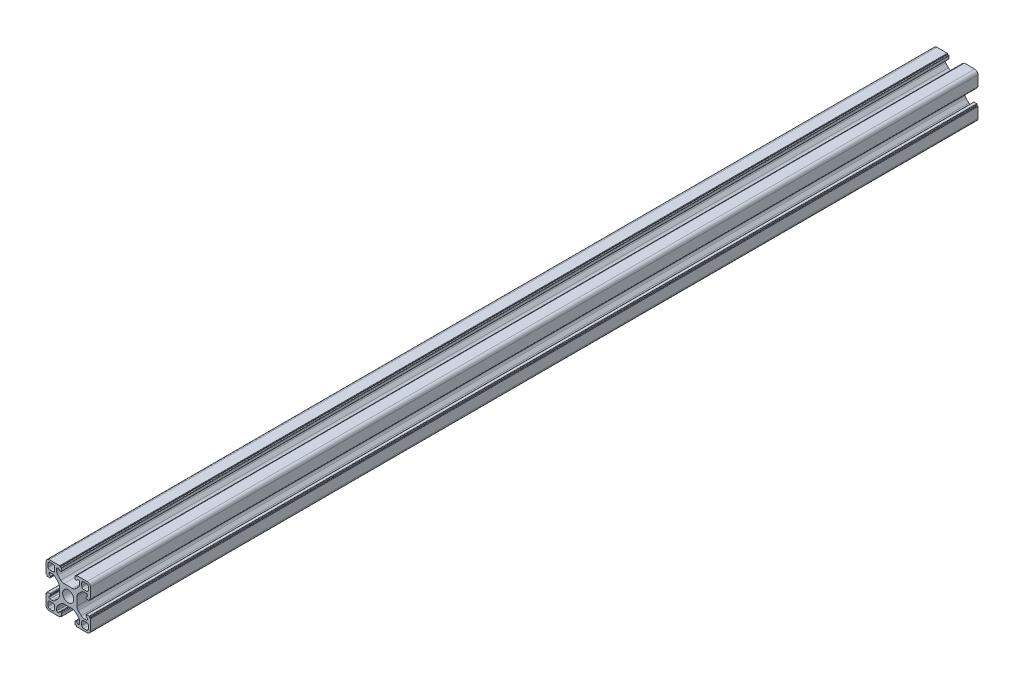
SolidWorks part; units mm, degrees
material "1060 Сплав"
ref_plane "Спереди" through (0, 0, 0) normal (0, 0, 1) x (1, 0, 0)
ref_plane "Сверху" through (0, 0, 0) normal (0, 1, 0) x (1, 0, 0)
ref_plane "Справа" through (0, 0, 0) normal (1, 0, 0) x (0, 0, -1)
sketch "Эскиз1" plane through (0, 0, 0) normal (0, 0, 1) x (1, 0, 0)
  line L0 (-22.0052, 70.3096) -> (-25.0052, 67.3096) construction
  line L1 (-31.1052, 65.2096) -> (-29.2064, 65.2096)
  line L2 (-31.1052, 61.2096) -> (-21.1052, 71.2096) construction
  line L3 (-23.5052, 68.8096) -> (-25.0052, 70.3096) construction
  line L4 (-27.7922, 65.7954) -> (-26.4909, 67.0967)
  line L5 (-24.2052, 67.3096) -> (-22.8052, 67.3096)
  line L6 (-25.0052, 68.1096) -> (-25.0052, 69.5096)
  line L7 (-22.8052, 70.3096) -> (-24.2052, 70.3096)
  line L8 (-25.9052, 69.4096) -> (-25.9052, 68.5109)
  line L9 (-27.3419, 69.2829) -> (-26.8616, 69.7632)
  line L10 (-27.9052, 70.7587) -> (-27.4052, 70.7587)
  line L11 (-27.5187, 69.2096) -> (-27.8052, 69.2096)
  line L12 (-26.508, 69.9096) -> (-26.4052, 69.9096)
  line L13 (-27.4052, 71.0596) -> (-27.4052, 70.7587)
  line L14 (-28.0552, 70.6087) -> (-28.0552, 69.4596)
  line L15 (-22.6052, 71.2096) -> (-27.2552, 71.2096)
  line L16 (-22.0052, 69.5096) -> (-22.0052, 68.1096)
  line L17 (-21.1052, 69.7096) -> (-21.1052, 65.0596)
  line L18 (-21.7061, 64.2596) -> (-22.8552, 64.2596)
  line L19 (-21.2552, 64.9096) -> (-21.5561, 64.9096)
  line L20 (-22.4052, 65.8068) -> (-22.4052, 65.9096)
  line L21 (-23.1052, 64.7961) -> (-23.1052, 64.5096)
  line L22 (-21.5561, 64.4096) -> (-21.5561, 64.9096)
  line L23 (-23.0319, 64.9729) -> (-22.5516, 65.4532)
  line L24 (-22.9052, 66.4096) -> (-23.8039, 66.4096)
  line L25 (-26.5194, 64.5226) -> (-25.2181, 65.8239)
  line L26 (-27.1052, 61.2096) -> (-27.1052, 63.1084)
  line L27 (-27.1052, 61.2096) -> (-27.1052, 59.3109)
  line L28 (-26.5194, 57.8967) -> (-25.2181, 56.5954)
  line L29 (-25.0052, 54.3096) -> (-25.0052, 52.9096)
  line L30 (-24.2052, 55.1096) -> (-22.8052, 55.1096)
  line L31 (-22.0052, 52.9096) -> (-22.0052, 54.3096)
  line L32 (-22.9052, 56.0096) -> (-23.8039, 56.0096)
  line L33 (-23.0319, 57.4464) -> (-22.5516, 56.9661)
  line L34 (-21.5561, 58.0096) -> (-21.5561, 57.5096)
  line L35 (-23.1052, 57.6232) -> (-23.1052, 57.9096)
  line L36 (-22.4052, 56.6125) -> (-22.4052, 56.5096)
  line L37 (-21.2552, 57.5096) -> (-21.5561, 57.5096)
  line L38 (-21.7061, 58.1596) -> (-22.8552, 58.1596)
  line L39 (-21.1052, 52.7096) -> (-21.1052, 57.3596)
  line L40 (-22.8052, 52.1096) -> (-24.2052, 52.1096)
  line L41 (-22.6052, 51.2096) -> (-27.2552, 51.2096)
  line L42 (-28.0552, 51.8106) -> (-28.0552, 52.9596)
  line L43 (-27.4052, 51.3596) -> (-27.4052, 51.6606)
  line L44 (-26.508, 52.5096) -> (-26.4052, 52.5096)
  line L45 (-27.5187, 53.2096) -> (-27.8052, 53.2096)
  line L46 (-27.9052, 51.6606) -> (-27.4052, 51.6606)
  line L47 (-27.3419, 53.1364) -> (-26.8616, 52.6561)
  line L48 (-25.9052, 53.0096) -> (-25.9052, 53.9084)
  line L49 (-27.7922, 56.6239) -> (-26.4909, 55.3226)
  line L50 (-31.1052, 57.2096) -> (-29.2064, 57.2096)
  line L51 (-22.0052, 52.1096) -> (-25.0052, 55.1096) construction
  line L52 (-31.1052, 61.2096) -> (-21.1052, 51.2096) construction
  line L53 (-23.5052, 53.6096) -> (-22.0052, 55.1096) construction
  line L54 (-31.1052, 57.2096) -> (-33.0039, 57.2096)
  line L55 (-34.4181, 56.6239) -> (-35.7194, 55.3226)
  line L56 (-38.0052, 55.1096) -> (-39.4052, 55.1096)
  line L57 (-37.2052, 54.3096) -> (-37.2052, 52.9096)
  line L58 (-39.4052, 52.1096) -> (-38.0052, 52.1096)
  line L59 (-36.3052, 53.0096) -> (-36.3052, 53.9084)
  line L60 (-34.8684, 53.1364) -> (-35.3487, 52.6561)
  line L61 (-34.3052, 51.6606) -> (-34.8052, 51.6606)
  line L62 (-34.6916, 53.2096) -> (-34.4052, 53.2096)
  line L63 (-35.7023, 52.5096) -> (-35.8052, 52.5096)
  line L64 (-34.8052, 51.3596) -> (-34.8052, 51.6606)
  line L65 (-34.1552, 51.8106) -> (-34.1552, 52.9596)
  line L66 (-39.6052, 51.2096) -> (-34.9552, 51.2096)
  line L67 (-40.2052, 52.9096) -> (-40.2052, 54.3096)
  line L68 (-41.1052, 52.7096) -> (-41.1052, 57.3596)
  line L69 (-40.5042, 58.1596) -> (-39.3552, 58.1596)
  line L70 (-40.9552, 57.5096) -> (-40.6542, 57.5096)
  line L71 (-39.8052, 56.6125) -> (-39.8052, 56.5096)
  line L72 (-39.1052, 57.6232) -> (-39.1052, 57.9096)
  line L73 (-40.6542, 58.0096) -> (-40.6542, 57.5096)
  line L74 (-39.1784, 57.4464) -> (-39.6587, 56.9661)
  line L75 (-39.3052, 56.0096) -> (-38.4064, 56.0096)
  line L76 (-35.6909, 57.8967) -> (-36.9922, 56.5954)
  line L77 (-35.1052, 61.2096) -> (-35.1052, 59.3109)
  line L78 (-40.2052, 52.1096) -> (-37.2052, 55.1096) construction
  line L79 (-31.1052, 61.2096) -> (-41.1052, 51.2096) construction
  line L80 (-38.7052, 53.6096) -> (-37.2052, 52.1096) construction
  line L81 (-35.1052, 61.2096) -> (-35.1052, 63.1084)
  line L82 (-35.6909, 64.5226) -> (-36.9922, 65.8239)
  line L83 (-37.2052, 68.1096) -> (-37.2052, 69.5096)
  line L84 (-38.0052, 67.3096) -> (-39.4052, 67.3096)
  line L85 (-40.2052, 69.5096) -> (-40.2052, 68.1096)
  line L86 (-39.3052, 66.4096) -> (-38.4064, 66.4096)
  line L87 (-39.1784, 64.9729) -> (-39.6587, 65.4532)
  line L88 (-40.6542, 64.4096) -> (-40.6542, 64.9096)
  line L89 (-39.1052, 64.7961) -> (-39.1052, 64.5096)
  line L90 (-39.8052, 65.8068) -> (-39.8052, 65.9096)
  line L91 (-40.9552, 64.9096) -> (-40.6542, 64.9096)
  line L92 (-40.5042, 64.2596) -> (-39.3552, 64.2596)
  line L93 (-41.1052, 69.7096) -> (-41.1052, 65.0596)
  line L94 (-39.4052, 70.3096) -> (-38.0052, 70.3096)
  line L95 (-39.6052, 71.2096) -> (-34.9552, 71.2096)
  line L96 (-34.1552, 70.6087) -> (-34.1552, 69.4596)
  line L97 (-34.8052, 71.0596) -> (-34.8052, 70.7587)
  line L98 (-35.7023, 69.9096) -> (-35.8052, 69.9096)
  line L99 (-34.6916, 69.2096) -> (-34.4052, 69.2096)
  line L100 (-34.3052, 70.7587) -> (-34.8052, 70.7587)
  line L101 (-34.8684, 69.2829) -> (-35.3487, 69.7632)
  line L102 (-36.3052, 69.4096) -> (-36.3052, 68.5109)
  line L103 (-34.4181, 65.7954) -> (-35.7194, 67.0967)
  line L104 (-31.1052, 65.2096) -> (-33.0039, 65.2096)
  line L105 (-42.8692, 61.2096) -> (-19.6008, 61.2096) construction
  line L106 (-40.2052, 70.3096) -> (-37.2052, 67.3096) construction
  line L107 (-31.1052, 49.1232) -> (-31.1052, 71.9286) construction
  line L108 (-31.1052, 61.2096) -> (-41.1052, 71.2096) construction
  line L109 (-38.7052, 68.8096) -> (-40.2052, 67.3096) construction
  arc A0 (-22.0052, 69.5096) -> (-22.8052, 70.3096) centre (-22.8052, 69.5096) ccw
  arc A1 (-24.2052, 70.3096) -> (-25.0052, 69.5096) centre (-24.2052, 69.5096) ccw
  arc A2 (-24.2052, 67.3096) -> (-25.0052, 68.1096) centre (-24.2052, 68.1096) cw
  arc A3 (-22.6052, 71.2096) -> (-21.1052, 69.7096) centre (-22.6052, 69.7096) cw
  arc A4 (-27.9052, 70.7587) -> (-28.0552, 70.6087) centre (-27.9052, 70.6087) ccw
  arc A5 (-27.2552, 71.2096) -> (-27.4052, 71.0596) centre (-27.2552, 71.0596) ccw
  arc A6 (-27.5187, 69.2096) -> (-27.3419, 69.2829) centre (-27.5187, 69.4596) ccw
  arc A7 (-27.8052, 69.2096) -> (-28.0552, 69.4596) centre (-27.8052, 69.4596) cw
  arc A8 (-26.8616, 69.7632) -> (-26.508, 69.9096) centre (-26.508, 69.4096) cw
  arc A9 (-26.4052, 69.9096) -> (-25.9052, 69.4096) centre (-26.4052, 69.4096) cw
  arc A10 (-28.6052, 61.2096) -> (-31.1052, 63.7096) centre (-31.1052, 61.2096) ccw
  arc A11 (-29.2064, 65.2096) -> (-27.7922, 65.7954) centre (-29.2064, 67.2096) ccw
  arc A12 (-25.9052, 68.5109) -> (-26.4909, 67.0967) centre (-27.9052, 68.5109) cw
  arc A13 (-22.0052, 68.1096) -> (-22.8052, 67.3096) centre (-22.8052, 68.1096) cw
  arc A14 (-22.4052, 65.9096) -> (-22.9052, 66.4096) centre (-22.9052, 65.9096) ccw
  arc A15 (-22.5516, 65.4532) -> (-22.4052, 65.8068) centre (-22.9052, 65.8068) ccw
  arc A16 (-23.1052, 64.5096) -> (-22.8552, 64.2596) centre (-22.8552, 64.5096) ccw
  arc A17 (-23.1052, 64.7961) -> (-23.0319, 64.9729) centre (-22.8552, 64.7961) cw
  arc A18 (-21.1052, 65.0596) -> (-21.2552, 64.9096) centre (-21.2552, 65.0596) cw
  arc A19 (-21.5561, 64.4096) -> (-21.7061, 64.2596) centre (-21.7061, 64.4096) cw
  arc A20 (-23.8039, 66.4096) -> (-25.2181, 65.8239) centre (-23.8039, 64.4096) ccw
  arc A21 (-27.1052, 63.1084) -> (-26.5194, 64.5226) centre (-25.1052, 63.1084) cw
  arc A22 (-22.8052, 52.1096) -> (-22.0052, 52.9096) centre (-22.8052, 52.9096) ccw
  arc A23 (-22.0052, 54.3096) -> (-22.8052, 55.1096) centre (-22.8052, 54.3096) ccw
  arc A24 (-25.0052, 54.3096) -> (-24.2052, 55.1096) centre (-24.2052, 54.3096) cw
  arc A25 (-21.1052, 52.7096) -> (-22.6052, 51.2096) centre (-22.6052, 52.7096) cw
  arc A26 (-21.5561, 58.0096) -> (-21.7061, 58.1596) centre (-21.7061, 58.0096) ccw
  arc A27 (-21.1052, 57.3596) -> (-21.2552, 57.5096) centre (-21.2552, 57.3596) ccw
  arc A28 (-23.1052, 57.6232) -> (-23.0319, 57.4464) centre (-22.8552, 57.6232) ccw
  arc A29 (-23.1052, 57.9096) -> (-22.8552, 58.1596) centre (-22.8552, 57.9096) cw
  arc A30 (-22.5516, 56.9661) -> (-22.4052, 56.6125) centre (-22.9052, 56.6125) cw
  arc A31 (-22.4052, 56.5096) -> (-22.9052, 56.0096) centre (-22.9052, 56.5096) cw
  arc A32 (-31.1052, 58.7096) -> (-28.6052, 61.2096) centre (-31.1052, 61.2096) ccw
  arc A33 (-27.1052, 59.3109) -> (-26.5194, 57.8967) centre (-25.1052, 59.3109) ccw
  arc A34 (-23.8039, 56.0096) -> (-25.2181, 56.5954) centre (-23.8039, 58.0096) cw
  arc A35 (-24.2052, 52.1096) -> (-25.0052, 52.9096) centre (-24.2052, 52.9096) cw
  arc A36 (-26.4052, 52.5096) -> (-25.9052, 53.0096) centre (-26.4052, 53.0096) ccw
  arc A37 (-26.8616, 52.6561) -> (-26.508, 52.5096) centre (-26.508, 53.0096) ccw
  arc A38 (-27.8052, 53.2096) -> (-28.0552, 52.9596) centre (-27.8052, 52.9596) ccw
  arc A39 (-27.5187, 53.2096) -> (-27.3419, 53.1364) centre (-27.5187, 52.9596) cw
  arc A40 (-27.2552, 51.2096) -> (-27.4052, 51.3596) centre (-27.2552, 51.3596) cw
  arc A41 (-27.9052, 51.6606) -> (-28.0552, 51.8106) centre (-27.9052, 51.8106) cw
  arc A42 (-25.9052, 53.9084) -> (-26.4909, 55.3226) centre (-27.9052, 53.9084) ccw
  arc A43 (-29.2064, 57.2096) -> (-27.7922, 56.6239) centre (-29.2064, 55.2096) cw
  arc A44 (-40.2052, 52.9096) -> (-39.4052, 52.1096) centre (-39.4052, 52.9096) ccw
  arc A45 (-38.0052, 52.1096) -> (-37.2052, 52.9096) centre (-38.0052, 52.9096) ccw
  arc A46 (-38.0052, 55.1096) -> (-37.2052, 54.3096) centre (-38.0052, 54.3096) cw
  arc A47 (-39.6052, 51.2096) -> (-41.1052, 52.7096) centre (-39.6052, 52.7096) cw
  arc A48 (-34.3052, 51.6606) -> (-34.1552, 51.8106) centre (-34.3052, 51.8106) ccw
  arc A49 (-34.9552, 51.2096) -> (-34.8052, 51.3596) centre (-34.9552, 51.3596) ccw
  arc A50 (-34.6916, 53.2096) -> (-34.8684, 53.1364) centre (-34.6916, 52.9596) ccw
  arc A51 (-34.4052, 53.2096) -> (-34.1552, 52.9596) centre (-34.4052, 52.9596) cw
  arc A52 (-35.3487, 52.6561) -> (-35.7023, 52.5096) centre (-35.7023, 53.0096) cw
  arc A53 (-35.8052, 52.5096) -> (-36.3052, 53.0096) centre (-35.8052, 53.0096) cw
  arc A54 (-33.6052, 61.2096) -> (-31.1052, 58.7096) centre (-31.1052, 61.2096) ccw
  arc A55 (-33.0039, 57.2096) -> (-34.4181, 56.6239) centre (-33.0039, 55.2096) ccw
  arc A56 (-36.3052, 53.9084) -> (-35.7194, 55.3226) centre (-34.3052, 53.9084) cw
  arc A57 (-40.2052, 54.3096) -> (-39.4052, 55.1096) centre (-39.4052, 54.3096) cw
  arc A58 (-39.8052, 56.5096) -> (-39.3052, 56.0096) centre (-39.3052, 56.5096) ccw
  arc A59 (-39.6587, 56.9661) -> (-39.8052, 56.6125) centre (-39.3052, 56.6125) ccw
  arc A60 (-39.1052, 57.9096) -> (-39.3552, 58.1596) centre (-39.3552, 57.9096) ccw
  arc A61 (-39.1052, 57.6232) -> (-39.1784, 57.4464) centre (-39.3552, 57.6232) cw
  arc A62 (-41.1052, 57.3596) -> (-40.9552, 57.5096) centre (-40.9552, 57.3596) cw
  arc A63 (-40.6542, 58.0096) -> (-40.5042, 58.1596) centre (-40.5042, 58.0096) cw
  arc A64 (-38.4064, 56.0096) -> (-36.9922, 56.5954) centre (-38.4064, 58.0096) ccw
  arc A65 (-35.1052, 59.3109) -> (-35.6909, 57.8967) centre (-37.1052, 59.3109) cw
  arc A66 (-39.4052, 70.3096) -> (-40.2052, 69.5096) centre (-39.4052, 69.5096) ccw
  arc A67 (-40.2052, 68.1096) -> (-39.4052, 67.3096) centre (-39.4052, 68.1096) ccw
  arc A68 (-37.2052, 68.1096) -> (-38.0052, 67.3096) centre (-38.0052, 68.1096) cw
  arc A69 (-41.1052, 69.7096) -> (-39.6052, 71.2096) centre (-39.6052, 69.7096) cw
  arc A70 (-40.6542, 64.4096) -> (-40.5042, 64.2596) centre (-40.5042, 64.4096) ccw
  arc A71 (-41.1052, 65.0596) -> (-40.9552, 64.9096) centre (-40.9552, 65.0596) ccw
  arc A72 (-39.1052, 64.7961) -> (-39.1784, 64.9729) centre (-39.3552, 64.7961) ccw
  arc A73 (-39.1052, 64.5096) -> (-39.3552, 64.2596) centre (-39.3552, 64.5096) cw
  arc A74 (-39.6587, 65.4532) -> (-39.8052, 65.8068) centre (-39.3052, 65.8068) cw
  arc A75 (-39.8052, 65.9096) -> (-39.3052, 66.4096) centre (-39.3052, 65.9096) cw
  arc A76 (-31.1052, 63.7096) -> (-33.6052, 61.2096) centre (-31.1052, 61.2096) ccw
  arc A77 (-35.1052, 63.1084) -> (-35.6909, 64.5226) centre (-37.1052, 63.1084) ccw
  arc A78 (-38.4064, 66.4096) -> (-36.9922, 65.8239) centre (-38.4064, 64.4096) cw
  arc A79 (-38.0052, 70.3096) -> (-37.2052, 69.5096) centre (-38.0052, 69.5096) cw
  arc A80 (-35.8052, 69.9096) -> (-36.3052, 69.4096) centre (-35.8052, 69.4096) ccw
  arc A81 (-35.3487, 69.7632) -> (-35.7023, 69.9096) centre (-35.7023, 69.4096) ccw
  arc A82 (-34.4052, 69.2096) -> (-34.1552, 69.4596) centre (-34.4052, 69.4596) ccw
  arc A83 (-34.6916, 69.2096) -> (-34.8684, 69.2829) centre (-34.6916, 69.4596) cw
  arc A84 (-34.9552, 71.2096) -> (-34.8052, 71.0596) centre (-34.9552, 71.0596) cw
  arc A85 (-34.3052, 70.7587) -> (-34.1552, 70.6087) centre (-34.3052, 70.6087) cw
  arc A86 (-36.3052, 68.5109) -> (-35.7194, 67.0967) centre (-34.3052, 68.5109) ccw
  arc A87 (-33.0039, 65.2096) -> (-34.4181, 65.7954) centre (-33.0039, 67.2096) cw
  point P0 (-31.1052, 61.2096)
  point P9 (-31.1052, 61.2096)
  point P40 (-22.4052, 64.9096)
  point P93 (-27.4052, 52.5096)
  point P144 (-27.4052, 69.9096)
  point P152 (-22.4052, 57.5096)
  point P153 (-31.1052, 57.2854)
  point P154 (-31.1052, 61.2096)
  point P189 (-39.8052, 57.5096)
  point P228 (-34.8052, 52.5096)
  point P229 (-35.0294, 61.2096)
  point P230 (-31.1052, 61.2096)
  point P268 (-34.8052, 69.9096)
  point P273 (-27.1809, 61.2096)
  point P306 (-39.8052, 64.9096)
  point P307 (-31.1052, 65.1339)
  point P309 (-31.1052, 61.2096)
  dimension "D3" = 5
  dimension "D6" = 2
  dimension "D1" = 2
  dimension "D2" = 6
  dimension "D4" = 4
  dimension "D5" = 0.9
extrude "Бобышка-Вытянуть1" add sketch "Эскиз1" along normal blind 400
